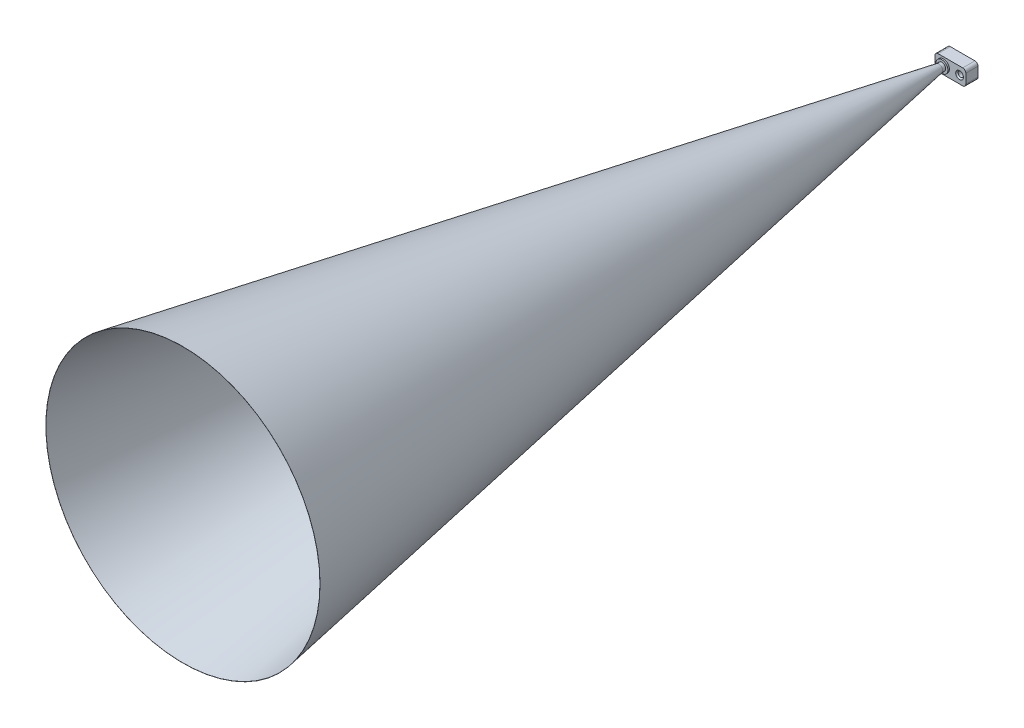
SolidWorks part; units mm, degrees
ref_plane "Front" through (0, 0, 0) normal (0, 0, 1) x (1, 0, 0)
ref_plane "Top" through (0, 0, 0) normal (0, 1, 0) x (1, 0, 0)
ref_plane "Right" through (0, 0, 0) normal (1, 0, 0) x (0, 0, -1)
sketch "Sketch1" plane through (0, 0, 0) normal (0, 0, 1) x (1, 0, 0)
  line L1 (0, 0) -> (20.066, 0)
  line L2 (0, 0) -> (0, 10.16)
  line L3 (0, 10.16) -> (20.066, 10.16)
  line L4 (20.066, 0) -> (20.066, 10.16)
  dimension "D1" = 20.066
  dimension "D2" = 10.16
extrude "Boss-Extrude1" add sketch "Sketch1" along normal blind 7.9502
sketch "Sketch2" plane through (0, 0, 7.9502) normal (0, 0, 1) x (1, 0, 0)
  line L0 (0, 10.16) -> (0, 0) construction
  line L1 (5.5, 10.16) -> (5.5, 0) construction
  line L2 (20.066, 10.16) -> (0, 10.16) construction
  line L3 (0, 0) -> (20.066, 0) construction
  circle A0 centre (5.5, 5.08) radius 3.8862
  dimension "D1" = 7.7724
  dimension "D2" = 5.5
extrude "Boss-Extrude2" add sketch "Sketch2" along normal blind 0.9906
sketch "Sketch3" plane through (0, 0, 8.9408) normal (0, 0, 1) x (1, 0, 0)
  circle A0 centre (5.5, 5.08) radius 2.4765
  dimension "D1" = 4.953
extrude "Boss-Extrude3" add sketch "Sketch3" along normal blind 4.2164
hole_wizard "CSK for M3 SFHCS1" positions "Sketch4" profile "Sketch5" countersink size "M3" standard "ANSI Metric" end condition through all
sketch "Sketch4" plane through (0, 0, 7.9502) normal (0, 0, 1) x (1, 0, 0)
  line L0 (16, 10.16) -> (16, 0) construction
  line L1 (20.066, 10.16) -> (0, 10.16) construction
  line L2 (0, 0) -> (20.066, 0) construction
  circle A0 centre (5.5, 5.08) radius 2.4765 construction
  point P0 (16, 5.08)
  dimension "D1" = 10.5
sketch "Sketch5" plane through (16, 5.08, 7.9502) normal (1, 0, 0) x (0, -1, 0)
  line L0 (0, 0) -> (0, 7.9502)
  line L1 (0, 7.9502) -> (1.7, 7.9502)
  line L2 (1.7, 7.9502) -> (1.7, 0.8)
  line L3 (1.7, 0.8) -> (2.5, 0)
  line L5 (2.5, 0) -> (0, 0)
  line L6 (-1.7, 0.8) -> (-2.5, 0) construction
  line L11 (0, -6.35) -> (0, 107.95) construction
  dimension "Thru Hole Dia." = 3.4
  dimension "Thru Hole Depth" = 7.9502
  dimension "Near C'Sink Dia." = 5
  dimension "Near C'Sink Angle" = 90
fillet "Fillet1" radius 2.286 1 edges at (7.9765, 5.08, 13.1572)
fillet "Fillet2" radius 2 4 edges at (0, 0, 3.9751) (0, 10.16, 3.9751) (20.066, 0, 3.9751) (20.066, 10.16, 3.9751)
ref_plane "Plane1" through (0, 5.08, 0) normal (0, 1, 0) x (1, 0, 0)
sketch "Sketch7" plane through (0, 5.08, 0) normal (0, 1, 0) x (1, 0, 0)
  line L0 (7.9765, -10.8712) -> (94.8006, -503.2751)
  line L1 (5.5, -13.1572) -> (5.5, -14.3589) construction
  line L2 (5.3095, -13.1572) -> (5.6905, -13.1572) construction
  line L3 (94.8006, -503.2751) -> (94.73, -503.2751)
  line L4 (94.73, -503.2751) -> (7.9059, -10.8712)
  line L5 (7.9059, -10.8712) -> (7.9765, -10.8712)
  line L6 (7.9765, -10.8712) -> (3.0235, -10.8712) construction
  arc A1 (5.6905, -13.1572) -> (7.9765, -10.8712) centre (5.6905, -10.8712) ccw construction
  dimension "D1" = 10
  dimension "D2" = 500
  dimension "D3" = 0.0706
revolve "Reciving View" add sketch "Sketch7" angle 360 about L1
sketch "Sketch8" [suppressed] plane through (0, 0, 13.1572) normal (0, 0, 1) x (1, 0, 0)
  circle A0 centre (5.5, 5.08) radius 0.1905 construction
  circle A1 centre (5.5, 5.08) radius 0.1905
extrude "Emission View" [suppressed] add sketch "Sketch8" along normal blind 500 separate body
